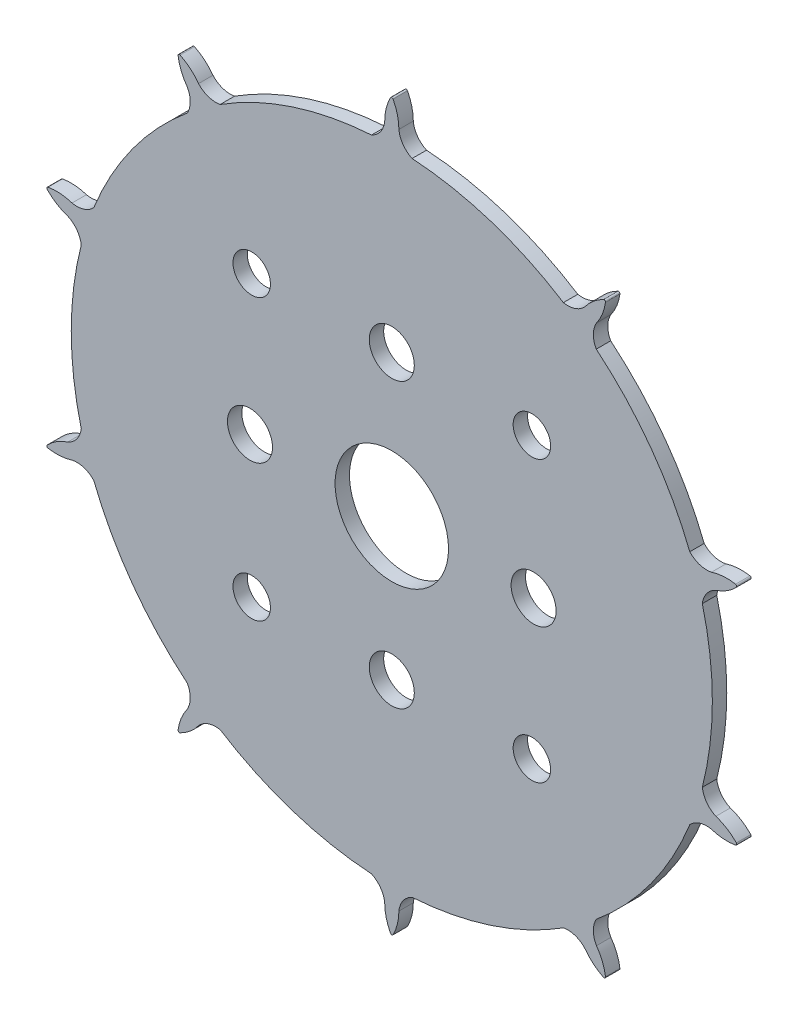
SolidWorks part; units mm, degrees
ref_plane "Front Plane" through (0, 0, 0) normal (0, 0, 1) x (1, 0, 0)
ref_plane "Top Plane" through (0, 0, 0) normal (0, 1, 0) x (1, 0, 0)
ref_plane "Right Plane" through (0, 0, 0) normal (1, 0, 0) x (0, 0, -1)
sketch "Sketch1" plane through (0, 0, 0) normal (0, 0, 1) x (1, 0, 0)
  circle A0 centre (0, 10) radius 1.5875
  circle A1 centre (0, 0) radius 22.6042
  circle A2 centre (9.8783, -9.8783) radius 1.3208
  circle A3 centre (9.8783, 9.8783) radius 1.3208
  circle A4 centre (-9.8783, -9.8783) radius 1.3208
  circle A5 centre (-9.8783, 9.8783) radius 1.3208
  circle A6 centre (0, 0) radius 4
  circle A7 centre (10, 0) radius 1.5875
  circle A8 centre (0, -10) radius 1.5875
  circle A9 centre (-10, 0) radius 1.5875
  dimension "D1" = 4
  dimension "D2" = 4
extrude "Boss-Extrude2" add sketch "Sketch1" along normal blind 1.016
sketch "Sketch2" plane through (0, 0, 1.016) normal (0, 0, 1) x (1, 0, 0)
  arc A0 (0.5, 23.868) -> (0.0883, 25.5178) centre (-3.0117, 23.868) ccw
  arc A1 (-0.5, 23.868) -> (-1.6391, 22.4794) centre (-2.1171, 24.0331) cw
  arc A2 (0.0883, 25.5178) -> (-0.0883, 25.5178) centre (0, 25.4708) ccw
  arc A3 (0.5, 23.868) -> (1.6391, 22.4794) centre (2.1172, 24.0331) ccw
  arc A4 (-1.6391, 22.4794) -> (1.6391, 22.4794) centre (0, 28.2138) ccw
  arc A5 (-0.5, 23.868) -> (-0.0883, 25.5178) centre (3.0118, 23.868) cw
extrude "Boss-Extrude4" add sketch "Sketch2" against normal blind 1.016
pattern_circular "CirPattern1" count 10 every 36 about axis through (0, 0, 0) along (0, 0, 1) of "Boss-Extrude4"
